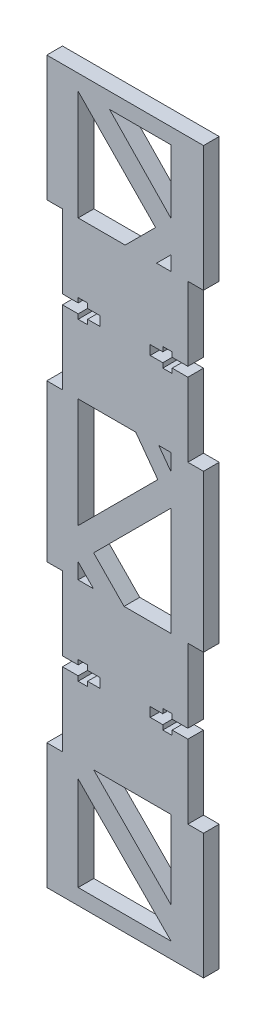
SolidWorks part; units mm, degrees
ref_plane "Front Plane" through (0, 0, 0) normal (0, 0, 1) x (1, 0, 0)
ref_plane "Top Plane" through (0, 0, 0) normal (0, 1, 0) x (1, 0, 0)
ref_plane "Right Plane" through (0, 0, 0) normal (1, 0, 0) x (0, 0, -1)
sketch "Sketch1" plane through (0, 0, 0) normal (0, 0, 1) x (1, 0, 0)
  line L1 (-25, 115) -> (25, 115)
  line L2 (-25, 115) -> (-25, -115)
  line L3 (-25, -115) -> (25, -115)
  line L4 (25, 115) -> (25, -115)
  line L5 (-25, 115) -> (25, -115) construction
  line L6 (-25, -115) -> (25, 115) construction
  point P0 (0, 0)
  dimension "D1" = 230
  dimension "D2" = 50
extrude "Boss-Extrude1" add sketch "Sketch1" along normal blind 5
sketch "Sketch9" plane through (0, 0, 5) normal (0, 0, 1) x (1, 0, 0)
  line L0 (-25, -115) -> (25, -115) construction
  line L1 (-25, 115) -> (-20, 115)
  line L2 (-25, 115) -> (-25, -115)
  line L3 (-25, -115) -> (-20, -115)
  line L4 (-20, 115) -> (-20, -115)
  line L6 (25, 115) -> (20, 115)
  line L7 (25, 115) -> (25, -115)
  line L8 (25, -115) -> (20, -115)
  line L9 (20, 115) -> (20, -115)
  line L10 (-25, 115) -> (-20, 115)
  line L11 (-25, 115) -> (-25, 75)
  line L12 (-25, 75) -> (-20, 75)
  line L13 (-20, 115) -> (-20, 75)
  line L14 (-25, -115) -> (-20, -115)
  line L15 (-25, -115) -> (-25, -75)
  line L16 (-25, -75) -> (-20, -75)
  line L17 (-20, -115) -> (-20, -75)
  line L18 (-25, 25) -> (-20, 25)
  line L19 (-25, 25) -> (-25, -25)
  line L20 (-25, -25) -> (-20, -25)
  line L21 (-20, 25) -> (-20, -25)
  line L22 (20, 115) -> (25, 115)
  line L23 (20, 115) -> (20, 75)
  line L24 (20, 75) -> (25, 75)
  line L25 (25, 115) -> (25, 75)
  line L26 (20, 25) -> (25, 25)
  line L27 (20, 25) -> (20, -25)
  line L28 (20, -25) -> (25, -25)
  line L29 (25, 25) -> (25, -25)
  line L30 (20, -115) -> (25, -115)
  line L31 (20, -115) -> (20, -75)
  line L32 (20, -75) -> (25, -75)
  line L33 (25, -115) -> (25, -75)
  dimension "D1" = 5
  dimension "D2" = 5
  dimension "D3" = 40
  dimension "D4" = 40
  dimension "D5" = 50
  dimension "D6" = 50
extrude "Cut-Extrude6" cut sketch "Sketch9" against normal blind 7 contours L2 L18 L4 L12 | L20 L2 L16 L4 | L9 L32 L7 L28 | L9 L26 L7 L24
sketch "Sketch10" plane through (-20, 0, 0) normal (-1, 0, 0) x (0, 0, 1)
  line L0 (2.5, 75) -> (2.5, 25) construction
  line L1 (0, 75) -> (5, 75) construction
  line L2 (0, 25) -> (5, 25) construction
  line L3 (2.5, -25) -> (2.5, -75) construction
  line L4 (0, -25) -> (5, -25) construction
  line L5 (0, -75) -> (5, -75) construction
  circle A0 centre (2.5, 50) radius 1.5
  circle A1 centre (2.5, -50) radius 1.5
extrude "Cut-Extrude7" cut sketch "Sketch10" against normal blind 7
sketch "Sketch11" plane through (20, 0, 0) normal (1, 0, 0) x (0, 0, -1)
  line L0 (-2.5, 75) -> (-2.5, 25) construction
  line L1 (0, 75) -> (-5, 75) construction
  line L2 (0, 25) -> (-5, 25) construction
  line L3 (-2.5, -25) -> (-2.5, -75) construction
  line L4 (0, -25) -> (-5, -25) construction
  line L5 (0, -75) -> (-5, -75) construction
  circle A0 centre (-2.5, -50) radius 1.5
  circle A1 centre (-2.5, 50) radius 1.5
extrude "Cut-Extrude8" cut sketch "Sketch11" against normal blind 7
sketch "Sketch12" plane through (0, 0, 5) normal (0, 0, 1) x (1, 0, 0)
  line L0 (-20, 75) -> (-20, 115) construction
  line L1 (25, 115) -> (-25, 115) construction
  line L2 (-20, 115) -> (-20, -115) construction
  line L3 (-25, -115) -> (25, -115) construction
  line L4 (20, 115) -> (20, -115) construction
  line L5 (-15, 110) -> (-15, -110) construction
  line L6 (14.6471, 110) -> (14.6471, -110) construction
  line L7 (-25, 110) -> (25, 110) construction
  line L8 (-25, 115) -> (-25, 75) construction
  line L9 (25, 75) -> (25, 115) construction
  line L10 (-25, -110) -> (25, -110) construction
  line L11 (-25, -75) -> (-25, -115) construction
  line L12 (25, -115) -> (25, -75) construction
  line L13 (-15, 110) -> (-15, -110)
  line L14 (-15, -110) -> (14.6471, -110)
  line L15 (14.6471, -110) -> (14.6471, 110)
  line L16 (14.6471, 110) -> (-15, 110)
  line L17 (-15, 110) -> (9.7059, 84.7059)
  line L18 (9.7059, 84.7059) -> (-15, 60)
  line L19 (14.6471, 79.6471) -> (-10.7647, 54.2353)
  line L20 (10.4118, 15.4118) -> (-15, -10)
  line L21 (-10.0588, -15.0588) -> (14.6471, -40.3529)
  line L22 (9.7059, -45.2941) -> (-15, -70)
  line L23 (-15, -80) -> (14.6471, -110)
  line L24 (-5, 110) -> (14.6471, 89.6471)
  line L25 (-10.7647, 54.2353) -> (14.6471, 19.6471)
  line L26 (14.6471, 9.6471) -> (-10.0588, -15.0588)
  line L27 (-15, -20) -> (9.7059, -45.2941)
  line L28 (-10.0296, -75.0296) -> (14.6471, -100)
  line L29 (14.6471, -50.3529) -> (-10.0296, -75.0296)
  line L31 (-15, 50) -> (10.4118, 15.4118)
  dimension "D2" = 10
  dimension "D3" = 5
  dimension "D4" = 5
  dimension "D5" = 10
  dimension "D6" = 50
  dimension "D7" = 60
  dimension "D8" = 50
  dimension "D10" = 10
  dimension "D12" = 10
  dimension "D14" = 10
  dimension "D16" = 10
extrude "Cut-Extrude9" cut sketch "Sketch12" against normal blind 7 contours L18 L17 L13 | L19 L25 L15 | L31 L13 L20 | L16 L24 L15 | L15 L26 L21 | L27 L13 L22 | L15 L29 L28 | L23 L13 L14
sketch "Sketch13" plane through (0, 0, 5) normal (0, 0, 1) x (1, 0, 0)
  line L1 (-20, -75) -> (20, -75)
  line L2 (-20, -75) -> (-20, -25)
  line L3 (-20, -25) -> (20, -25)
  line L4 (20, -75) -> (20, -25)
  line L5 (-20, 25) -> (20, 25)
  line L6 (-20, 25) -> (-20, 75)
  line L7 (-20, 75) -> (20, 75)
  line L8 (20, 25) -> (20, 75)
extrude "Boss-Extrude2" add sketch "Sketch13" against normal blind 5
sketch "Sketch14" plane through (0, 0, 5) normal (0, 0, 1) x (1, 0, 0)
  line L0 (-8, -50) -> (8, -50) construction
  line L1 (-20, -25) -> (-20, -75) construction
  line L2 (20, -25) -> (20, -75) construction
  line L3 (-8, 50) -> (8, 50) construction
  line L4 (-20, 75) -> (-20, 25) construction
  line L5 (20, 75) -> (20, 25) construction
  line L6 (2.3235, -75) -> (2.3235, 115) construction
  line L7 (-10, -75) -> (14.6471, -75) construction
  line L8 (25, 115) -> (-25, 115) construction
  line L9 (-15, -48.5) -> (-15, -47)
  line L10 (-20, -51.5) -> (-15, -51.5)
  line L11 (-20, -51.5) -> (-20, -48.5)
  line L12 (-20, -48.5) -> (-15, -48.5)
  line L13 (-8, -51.5) -> (-8, -48.5)
  line L14 (-15, -53) -> (-12, -53)
  line L15 (-15, -53) -> (-15, -51.5)
  line L16 (-15, -47) -> (-12, -47)
  line L17 (-12, -53) -> (-12, -51.5)
  line L18 (-20, 48.5) -> (-15, 48.5)
  line L19 (-20, 48.5) -> (-20, 51.5)
  line L20 (-20, 51.5) -> (-15, 51.5)
  line L21 (-8, 48.5) -> (-8, 51.5)
  line L22 (-15, 47) -> (-12, 47)
  line L23 (-15, 47) -> (-15, 48.5)
  line L24 (-15, 53) -> (-12, 53)
  line L25 (-12, 47) -> (-12, 48.5)
  line L26 (-12, -48.5) -> (-12, -47)
  line L27 (-12, -51.5) -> (-8, -51.5)
  line L28 (-12, -48.5) -> (-8, -48.5)
  line L29 (-12, 48.5) -> (-8, 48.5)
  line L30 (-12, 51.5) -> (-8, 51.5)
  line L31 (-15, 51.5) -> (-15, 53)
  line L32 (-12, 51.5) -> (-12, 53)
  line L33 (15, -48.5) -> (15, -47)
  line L34 (20, 48.5) -> (15, 48.5)
  line L35 (20, 48.5) -> (20, 51.5)
  line L36 (20, 51.5) -> (15, 51.5)
  line L37 (8, 48.5) -> (8, 51.5)
  line L38 (12, 47) -> (15, 47)
  line L39 (12, 47) -> (12, 48.5)
  line L40 (12, 53) -> (15, 53)
  line L41 (15, 47) -> (15, 48.5)
  line L42 (20, -51.5) -> (15, -51.5)
  line L43 (20, -51.5) -> (20, -48.5)
  line L44 (20, -48.5) -> (15, -48.5)
  line L45 (8, -51.5) -> (8, -48.5)
  line L46 (15, -53) -> (12, -53)
  line L47 (15, -53) -> (15, -51.5)
  line L48 (15, -47) -> (12, -47)
  line L49 (12, -53) -> (12, -51.5)
  line L50 (12, -48.5) -> (12, -47)
  line L51 (12, -51.5) -> (8, -51.5)
  line L52 (12, -48.5) -> (8, -48.5)
  line L53 (12, 50) -> (20, 50) construction
  line L54 (12, 51.5) -> (12, 53)
  line L55 (15, 51.5) -> (15, 53)
  line L56 (12, 48.5) -> (8, 48.5)
  line L57 (12, 51.5) -> (8, 51.5)
  dimension "D2" = 12
  dimension "D3" = 3
  dimension "D4" = 5
  dimension "D5" = 3
  dimension "D6" = 5
  dimension "D7" = 3
  dimension "D8" = 12
  dimension "D9" = 5
  dimension "D10" = 3
  dimension "D11" = 3
  dimension "D12" = 5
  dimension "D13" = 12
extrude "Cut-Extrude10" cut sketch "Sketch14" against normal blind 5
